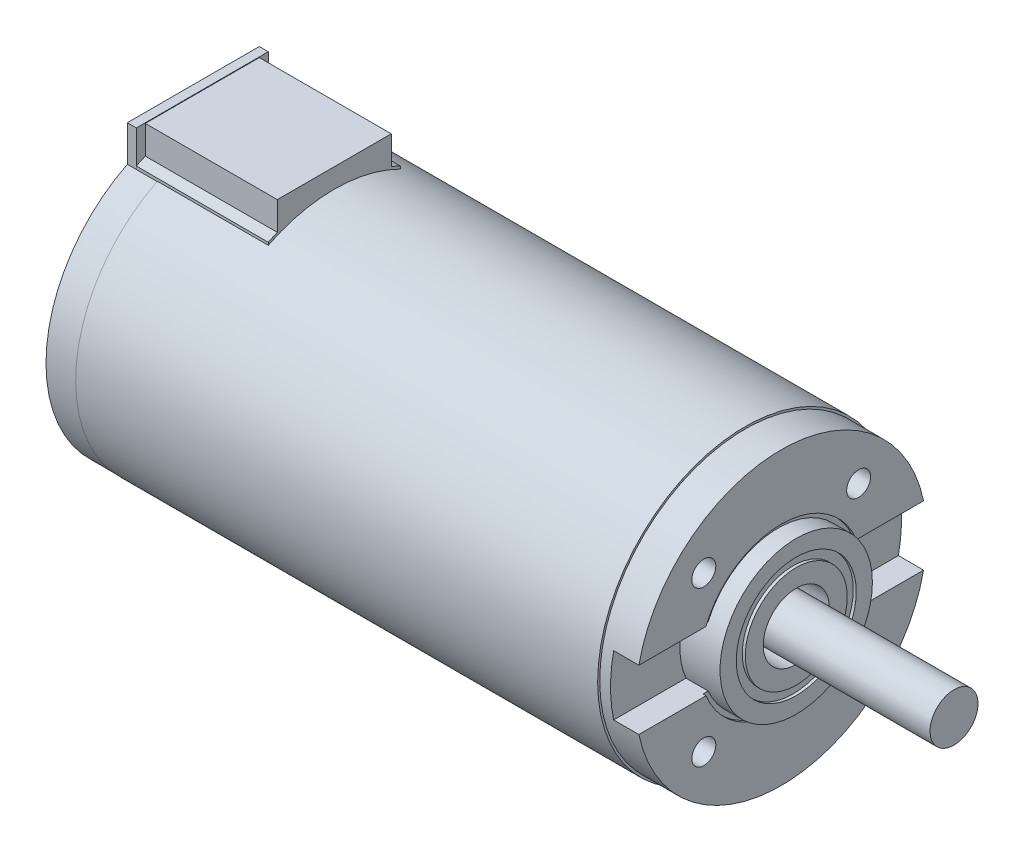
SolidWorks part; units mm, degrees
ref_plane "Front Plane" through (0, 0, 0) normal (0, 0, 1) x (1, 0, 0)
ref_plane "Top Plane" through (0, 0, 0) normal (0, 1, 0) x (1, 0, 0)
ref_plane "Right Plane" through (0, 0, 0) normal (1, 0, 0) x (0, 0, -1)
sketch "Sketch1" plane through (0, 0, 0) normal (1, 0, 0) x (0, 0, -1)
  circle A0 centre (0, 0) radius 24.6
  dimension "D1" = 49.2
extrude "Boss-Extrude1" add sketch "Sketch1" against normal blind 87
sketch "Sketch2" plane through (0, 0, 0) normal (1, 0, 0) x (0, 0, -1)
  circle A0 centre (0, 0) radius 24.25
  dimension "D1" = 48.5
extrude "Boss-Extrude2" add sketch "Sketch2" along normal blind 6
sketch "Sketch3" plane through (-87, 0, 0) normal (-1, 0, 0) x (0, 0, 1)
  line L0 (0, 0) -> (0, 40.0851) construction
  line L1 (11, 27.9477) -> (-11, 27.9477)
  line L2 (-11, 27.9477) -> (-11, 21.9477)
  line L3 (11, 27.9477) -> (11, 21.9477)
  arc A0 (-11, 21.9477) -> (11, 21.9477) centre (0, 0) ccw
  point P8 (0, 27.9477)
  dimension "D1" = 49.1
  dimension "D2" = 11
  dimension "D3" = 6
extrude "Boss-Extrude3" add sketch "Sketch3" along normal blind 5
sketch "Sketch4" plane through (6, 0, 0) normal (1, 0, 0) x (0, 0, -1)
  line L0 (-24.6, 0) -> (24.6, 0) construction
  line L1 (-23.7289, 5) -> (-11.6743, 5)
  line L2 (-23.7289, -5) -> (-11.6743, -5)
  line L3 (11.6743, -5) -> (23.7289, -5)
  line L4 (11.6743, 5) -> (23.7289, 5)
  line L5 (-12.9047, 12.9047) -> (0, 0) construction
  arc A0 (-11.6743, 5) -> (-11.6743, -5) centre (0, 0) ccw
  circle A1 centre (0, 0) radius 24.6 construction
  circle A2 centre (0, 0) radius 24.25 construction
  arc A3 (-23.7289, 5) -> (-23.7289, -5) centre (0, 0) ccw
  arc A4 (23.7289, -5) -> (23.7289, 5) centre (0, 0) ccw
  arc A5 (11.6743, -5) -> (11.6743, 5) centre (0, 0) ccw
  circle A6 centre (0, 0) radius 5.5
  circle A8 centre (-12.9047, 12.9047) radius 2
  circle A9 centre (12.9047, 12.9047) radius 2
  circle A10 centre (12.9047, -12.9047) radius 2
  circle A11 centre (-12.9047, -12.9047) radius 2
  point P2 (-15.5084, -12.6351)
  point P11 (0, 0)
  point P28 (0, 0)
  dimension "D1" = 25.4
  dimension "D3" = 11
  dimension "D5" = 4
  dimension "D2" = 5
  dimension "D4" = 5
  dimension "D6" = 45
  dimension "D7" = 18.25
  dimension "D8" = 4
extrude "Cut-Extrude1" cut sketch "Sketch4" against normal blind 4.2
sketch "Sketch5" plane through (6, 0, 0) normal (1, 0, 0) x (0, 0, -1)
  line L0 (-11.6743, 5) -> (-12.5399, 5)
  line L1 (-11.6743, 5) -> (-23.7289, 5) construction
  line L2 (-11.6743, -5) -> (-12.5399, -5)
  line L3 (-23.7289, -5) -> (-11.6743, -5) construction
  line L4 (11.6743, -5) -> (12.5399, -5)
  line L5 (11.6743, -5) -> (23.7289, -5) construction
  line L6 (11.6743, 5) -> (12.5399, 5)
  line L7 (23.7289, 5) -> (11.6743, 5) construction
  arc A0 (11.6743, 5) -> (-11.6743, 5) centre (0, 0) ccw
  arc A1 (12.5399, 5) -> (-12.5399, 5) centre (0, 0) ccw
  arc A2 (-12.5399, -5) -> (12.5399, -5) centre (0, 0) ccw
  arc A3 (-11.6743, -5) -> (11.6743, -5) centre (0, 0) ccw
  dimension "D1" = 27
extrude "Cut-Extrude2" cut sketch "Sketch5" against normal blind 0.5
sketch "Sketch6" plane through (6, 0, 0) normal (1, 0, 0) x (0, 0, -1)
  circle A0 centre (0, 0) radius 12.7
  circle A1 centre (0, 0) radius 5.5
extrude "Boss-Extrude4" add sketch "Sketch6" along normal blind 2.5
sketch "Sketch7" plane through (8.5, 0, 0) normal (1, 0, 0) x (0, 0, -1)
  circle A0 centre (0, 0) radius 10
  circle A1 centre (0, 0) radius 8.5
  dimension "D1" = 20
  dimension "D2" = 17
extrude "Cut-Extrude3" cut sketch "Sketch7" against normal blind 0.5
sketch "Sketch8" plane through (1.8, 0, 0) normal (1, 0, 0) x (0, 0, -1)
  circle A0 centre (0, 0) radius 4
  dimension "D1" = 8
extrude "Boss-Extrude5" add sketch "Sketch8" along normal blind 33
sketch "Sketch9" plane through (-87, 0, 0) normal (1, 0, 0) x (0, 0, -1)
  line L6 (11, 21.9477) -> (11, 27.9477)
  line L7 (11, 27.9477) -> (-11, 27.9477)
  line L8 (-11, 27.9477) -> (-11, 21.9477)
  arc A4 (11, 21.9477) -> (-11, 21.9477) centre (0, 0) ccw
extrude "Cut-Extrude4" cut sketch "Sketch9" against normal blind 3.5
sketch "Sketch11" plane through (-90.5, 0, 0) normal (1, 0, 0) x (0, 0, -1)
  line L0 (0, 0) -> (0, 27.9477) construction
  line L1 (11, 27.9477) -> (-11, 27.9477) construction
  line L3 (-9.5, 27.8477) -> (-9.5, 23.1247)
  line L4 (-11.0025, 22.4487) -> (-11, 21.9477)
  line L5 (-11, 27.9477) -> (-11, 21.9477) construction
  line L6 (9.5, 27.8477) -> (9.5, 23.1247)
  line L7 (11.0025, 22.4487) -> (11, 21.9477)
  line L8 (-9.5, 27.8477) -> (9.5, 27.8477)
  arc A0 (-9.5, 23.1247) -> (-11.0025, 22.4487) centre (0, 0) ccw
  arc A1 (11, 21.9477) -> (-11, 21.9477) centre (0, 0) ccw construction
  arc A2 (11, 21.9477) -> (-11, 21.9477) centre (0, 0) ccw
  arc A3 (9.5, 23.1247) -> (11.0025, 22.4487) centre (0, 0) cw
  dimension "D1" = 50
  dimension "D2" = 1.5
  dimension "D3" = 0.1
extrude "Boss-Extrude7" add sketch "Sketch11" along normal blind 22
sketch "Sketch12" plane through (0, 0, 0) normal (0, 0, 1) x (1, 0, 0)
  line L0 (0, 0) -> (-127.6331, 0) construction
  line L1 (-92, 4) -> (-97, 4)
  line L2 (-92, 21.9477) -> (-92, -24.55) construction
  line L3 (-97, 4) -> (-97, 2.5)
  line L4 (-97, 2.5) -> (-107, 2.5)
  line L5 (-107, 2.5) -> (-107, 0)
  line L6 (-107, 0) -> (-92, 0)
  line L7 (-92, 0) -> (-92, 4)
  dimension "D1" = 15
  dimension "D2" = 4
  dimension "D3" = 2.5
  dimension "D4" = 10
revolve "Revolve1" add sketch "Sketch12" angle 360 about L0
